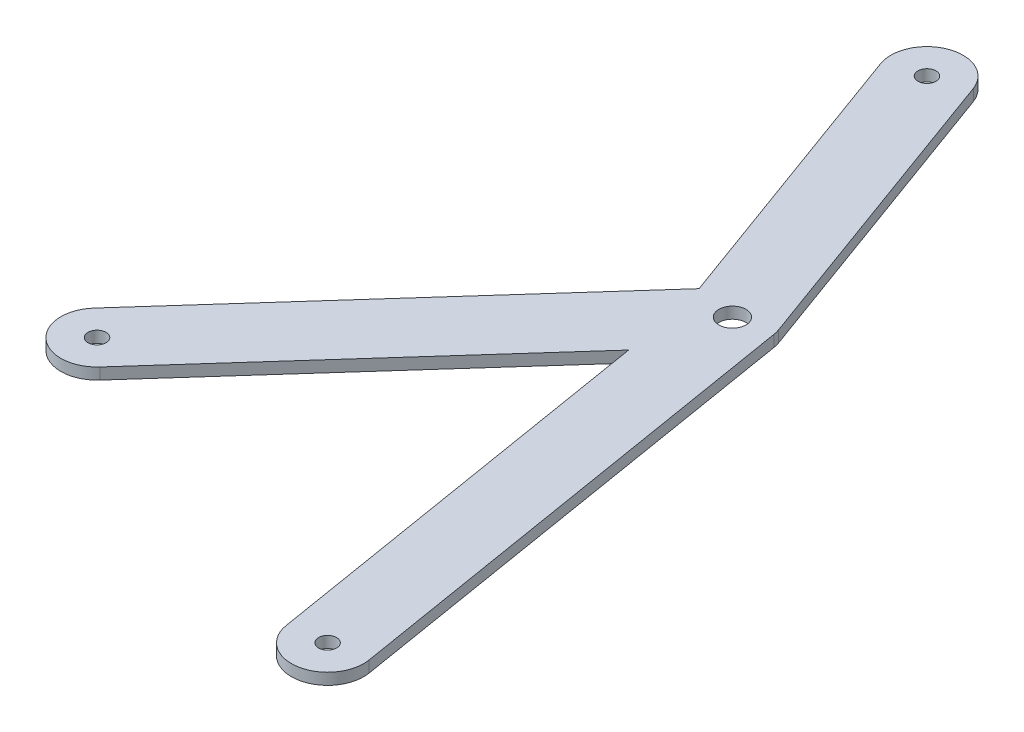
SolidWorks part; units mm, degrees
ref_plane "Front Plane" through (0, 0, 0) normal (0, 0, 1) x (1, 0, 0)
ref_plane "Top Plane" through (0, 0, 0) normal (0, 1, 0) x (1, 0, 0)
ref_plane "Right Plane" through (0, 0, 0) normal (1, 0, 0) x (0, 0, -1)
sketch "Sketch1" plane through (0, 0, 0) normal (0, 1, 0) x (1, 0, 0)
  line L1 (-55.0781, 65.6704) -> (-15.8825, -41.9018)
  line L2 (-78.9432, 56.9747) -> (-42.3518, -43.4503)
  line L6 (-42.3518, -43.4503) -> (-142.7448, -155.6549)
  line L8 (-15.283, -44.1907) -> (12.6912, -214.4599)
  line L10 (-36.0449, -74.4942) -> (-12.3728, -218.5777)
  line L11 (-36.0449, -74.4942) -> (-123.8156, -172.5914)
  arc A0 (-55.0781, 65.6704) -> (-78.9432, 56.9747) centre (-67.0106, 61.3226) ccw
  arc A3 (-142.7448, -155.6549) -> (-123.8156, -172.5914) centre (-133.2802, -164.1232) ccw
  arc A5 (-12.3728, -218.5777) -> (12.6912, -214.4599) centre (0.1592, -216.5188) ccw
  arc A6 (-15.8825, -41.9018) -> (-15.283, -44.1907) centre (-27.815, -46.2496) cw
  point P2 (-47.4128, 7.5365)
  point P10 (-27.815, -46.2496)
  point P12 (-80.5476, -105.1864)
  point P19 (-13.8279, -131.3842)
  dimension "D2" = 12.7
extrude "Boss-Extrude1" add sketch "Sketch1" along normal blind 4
sketch "Sketch5" plane through (0, 4, 0) normal (0, 1, 0) x (1, 0, 0)
  circle A0 centre (-27.815, -46.2496) radius 4.7625
  dimension "D1" = 9.525
extrude "Cut-Extrude1" cut sketch "Sketch5" against normal through all
sketch "Sketch8" plane through (0, 4, 0) normal (0, 1, 0) x (1, 0, 0)
  line L0 (-27.815, -46.2496) -> (-67.0106, 61.3226) construction
  line L1 (-27.815, -46.2496) -> (0.1592, -216.5188) construction
  line L2 (-27.815, -46.2496) -> (-133.2802, -164.1232) construction
  circle A0 centre (-67.0106, 61.3226) radius 3.175
  circle A1 centre (0.1592, -216.5188) radius 3.175
  circle A2 centre (-133.2802, -164.1232) radius 3.175
  dimension "D1" = 6.35
  dimension "D2" = 6.35
  dimension "D3" = 6.35
extrude "Cut-Extrude3" cut sketch "Sketch8" against normal through all
